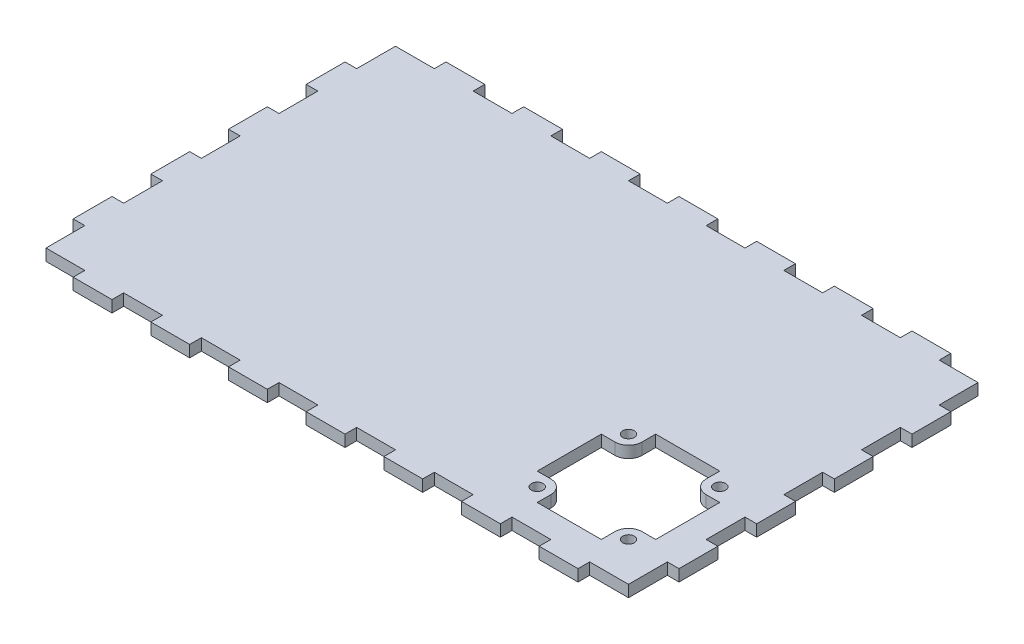
SolidWorks part; units mm, degrees
ref_plane "Front Plane" through (0, 0, 0) normal (0, 0, 1) x (1, 0, 0)
ref_plane "Top Plane" through (0, 0, 0) normal (0, 1, 0) x (1, 0, 0)
ref_plane "Right Plane" through (0, 0, 0) normal (1, 0, 0) x (0, 0, -1)
sketch "Sketch1" plane through (0, 0, 0) normal (0, 1, 0) x (1, 0, 0)
  line L0 (15, 45) -> (25, 48) construction
  line L1 (-76.5, 46.5) -> (76.5, 46.5) construction
  line L2 (-76.5, 46.5) -> (-76.5, -46.5) construction
  line L3 (-76.5, -46.5) -> (76.5, -46.5) construction
  line L4 (76.5, 46.5) -> (76.5, -46.5) construction
  line L5 (-76.5, 46.5) -> (76.5, -46.5) construction
  line L6 (-76.5, -46.5) -> (76.5, 46.5) construction
  line L7 (-5, 48) -> (5, 48)
  line L8 (-5, 48) -> (-5, 45)
  line L9 (-5, 45) -> (5, 45) construction
  line L10 (5, 48) -> (5, 45)
  line L11 (-5, 48) -> (5, 45) construction
  line L12 (-5, 45) -> (5, 48) construction
  line L13 (15, 45) -> (25, 45) construction
  line L14 (15, 48) -> (25, 45) construction
  line L15 (25, 48) -> (25, 45)
  line L16 (15, 48) -> (25, 48)
  line L17 (15, 48) -> (15, 45)
  line L18 (35, 45) -> (45, 48) construction
  line L19 (35, 45) -> (45, 45) construction
  line L20 (35, 48) -> (45, 45) construction
  line L21 (45, 48) -> (45, 45)
  line L22 (35, 48) -> (45, 48)
  line L23 (35, 48) -> (35, 45)
  line L24 (55, 45) -> (65, 48) construction
  line L25 (55, 45) -> (65, 45) construction
  line L26 (55, 48) -> (65, 45) construction
  line L27 (65, 48) -> (65, 45)
  line L28 (55, 48) -> (65, 48)
  line L29 (55, 48) -> (55, 45)
  line L30 (-25, 45) -> (-15, 48) construction
  line L31 (-25, 45) -> (-15, 45) construction
  line L32 (-25, 48) -> (-15, 45) construction
  line L33 (-15, 48) -> (-15, 45)
  line L34 (-25, 48) -> (-15, 48)
  line L35 (-25, 48) -> (-25, 45)
  line L36 (-45, 45) -> (-35, 48) construction
  line L37 (-45, 45) -> (-35, 45) construction
  line L38 (-45, 48) -> (-35, 45) construction
  line L39 (-35, 48) -> (-35, 45)
  line L40 (-45, 48) -> (-35, 48)
  line L41 (-45, 48) -> (-45, 45)
  line L42 (-65, 45) -> (-55, 48) construction
  line L43 (-65, 45) -> (-55, 45) construction
  line L44 (-65, 48) -> (-55, 45) construction
  line L45 (-55, 48) -> (-55, 45)
  line L46 (-65, 48) -> (-55, 48)
  line L47 (-65, 48) -> (-65, 45)
  line L48 (-55, 45) -> (-45, 45)
  line L49 (-35, 45) -> (-25, 45)
  line L50 (-15, 45) -> (-5, 45)
  line L51 (5, 45) -> (15, 45)
  line L52 (25, 45) -> (35, 45)
  line L53 (45, 45) -> (55, 45)
  line L54 (55, 48) -> (45, 48) construction
  line L55 (0, 0) -> (9.7796, 0) construction
  line L56 (0, 0) -> (0, 12.2502) construction
  line L57 (65, -48) -> (65, -45)
  line L58 (55, -48) -> (65, -48)
  line L59 (55, -48) -> (55, -45)
  line L60 (45, -45) -> (55, -45)
  line L61 (45, -48) -> (45, -45)
  line L62 (35, -48) -> (45, -48)
  line L63 (35, -48) -> (35, -45)
  line L64 (25, -45) -> (35, -45)
  line L65 (25, -48) -> (25, -45)
  line L66 (15, -48) -> (25, -48)
  line L67 (15, -48) -> (15, -45)
  line L68 (5, -45) -> (15, -45)
  line L69 (5, -48) -> (5, -45)
  line L70 (-5, -48) -> (5, -48)
  line L71 (-5, -48) -> (-5, -45)
  line L72 (-15, -45) -> (-5, -45)
  line L73 (-15, -48) -> (-15, -45)
  line L74 (-25, -48) -> (-15, -48)
  line L75 (-25, -48) -> (-25, -45)
  line L76 (-35, -45) -> (-25, -45)
  line L77 (-35, -48) -> (-35, -45)
  line L78 (-45, -48) -> (-35, -48)
  line L79 (-45, -48) -> (-45, -45)
  line L80 (-55, -45) -> (-45, -45)
  line L81 (-55, -48) -> (-55, -45)
  line L82 (-65, -48) -> (-65, -45)
  line L83 (-65, -48) -> (-55, -48)
  line L84 (-65, 45) -> (-75, 45)
  line L89 (-75, 45) -> (-75, 35)
  line L90 (-75, 25) -> (-75, 15)
  line L91 (-78, 25) -> (-75, 25)
  line L92 (-78, 25) -> (-78, 35)
  line L93 (-78, 35) -> (-75, 35)
  line L94 (-75, 25) -> (-75, 35) construction
  line L95 (-78, 25) -> (-75, 35) construction
  line L96 (-78, 35) -> (-75, 25) construction
  line L97 (-78, 5) -> (-75, 5)
  line L98 (-78, 5) -> (-75, 15) construction
  line L99 (-78, 5) -> (-78, 15)
  line L100 (-78, 15) -> (-75, 5) construction
  line L101 (-78, 15) -> (-75, 15)
  line L102 (-75, 5) -> (-75, 15) construction
  line L103 (-78, -15) -> (-75, -15)
  line L104 (-78, -15) -> (-75, -5) construction
  line L105 (-78, -15) -> (-78, -5)
  line L106 (-78, -5) -> (-75, -15) construction
  line L107 (-78, -5) -> (-75, -5)
  line L108 (-75, -15) -> (-75, -5) construction
  line L109 (-78, -35) -> (-75, -35)
  line L110 (-78, -35) -> (-75, -25) construction
  line L111 (-78, -35) -> (-78, -25)
  line L112 (-78, -25) -> (-75, -35) construction
  line L113 (-78, -25) -> (-75, -25)
  line L114 (-75, -35) -> (-75, -25) construction
  line L115 (-75, 5) -> (-75, -5)
  line L116 (-75, -15) -> (-75, -25)
  line L117 (-75, -35) -> (-75, -45)
  line L118 (-75, -45) -> (-65, -45)
  line L119 (65, 45) -> (75, 45)
  line L120 (65, -45) -> (75, -45)
  line L121 (75, -35) -> (75, -45)
  line L122 (78, -35) -> (75, -35)
  line L123 (78, -35) -> (78, -25)
  line L124 (78, -25) -> (75, -25)
  line L125 (75, -15) -> (75, -25)
  line L126 (78, -15) -> (75, -15)
  line L127 (78, -15) -> (78, -5)
  line L128 (78, -5) -> (75, -5)
  line L129 (75, 5) -> (75, -5)
  line L130 (78, 5) -> (75, 5)
  line L131 (78, 5) -> (78, 15)
  line L132 (78, 15) -> (75, 15)
  line L133 (75, 25) -> (75, 15)
  line L134 (78, 25) -> (75, 25)
  line L135 (78, 25) -> (78, 35)
  line L136 (78, 35) -> (75, 35)
  line L137 (75, 45) -> (75, 35)
  point P0 (0, 0)
  point P6 (0, 46.5)
  point P66 (-76.5, 30)
  dimension "D1" = 153
  dimension "D2" = 93
  dimension "D3" = 10
  dimension "D4" = 3
  dimension "D5" = 4
  dimension "D7" = 10
  dimension "D8" = 10
  dimension "D9" = 10
  dimension "D10" = 10
  dimension "D11" = 10
  dimension "D12" = 10
  dimension "D6" = 4
  dimension "D13" = 4
extrude "Boss-Extrude1" add sketch "Sketch1" along normal blind 3
sketch "Sketch3" plane through (0, 3, 0) normal (0, 1, 0) x (1, 0, 0)
  line L0 (41.5, -35) -> (41.5, -11.5) construction
  line L1 (41.5, -11.5) -> (65, -11.5) construction
  line L2 (65, -11.5) -> (65, -35) construction
  line L3 (65, -35) -> (41.5, -35) construction
  line L4 (45, -45) -> (55, -45) construction
  line L5 (75, -25) -> (75, -15) construction
  circle A0 centre (41.5, -11.5) radius 1.5
  circle A1 centre (65, -11.5) radius 1.5
  circle A2 centre (65, -35) radius 1.5
  circle A3 centre (41.5, -35) radius 1.5
  point P8 (61.6737, -9.3532)
  dimension "D1" = 3
  dimension "D2" = 3
  dimension "D3" = 3
  dimension "D4" = 3
  dimension "D5" = 23.5
  dimension "D6" = 23.5
  dimension "D7" = 10
  dimension "D8" = 10
extrude "Cut-Extrude2" cut sketch "Sketch3" against normal blind 3
sketch "Sketch4" plane through (0, 3, 0) normal (0, 1, 0) x (1, 0, 0)
  line L0 (41.5, -8) -> (65, -8) construction
  line L1 (38, -11.5) -> (38, -35) construction
  line L2 (41.5, -38.5) -> (65, -38.5) construction
  line L3 (68.5, -35) -> (68.5, -11.5) construction
  line L4 (45, -35) -> (45, -38.5)
  line L5 (61.5, -35) -> (61.5, -38.5)
  line L6 (65, -15) -> (68.5, -15)
  line L7 (65, -31.5) -> (68.5, -31.5)
  line L8 (41.5, -15) -> (38, -15)
  line L9 (41.5, -31.5) -> (38, -31.5)
  line L10 (45, -11.5) -> (45, -8)
  line L11 (61.5, -11.5) -> (61.5, -8)
  line L12 (38, -15) -> (38, -31.5)
  line L13 (45, -38.5) -> (61.5, -38.5)
  line L14 (68.5, -31.5) -> (68.5, -15)
  line L15 (61.5, -8) -> (45, -8)
  circle A0 centre (41.5, -11.5) radius 3.5 construction
  circle A1 centre (65, -11.5) radius 3.5 construction
  circle A2 centre (65, -35) radius 3.5 construction
  circle A3 centre (41.5, -35) radius 3.5 construction
  arc A4 (61.5, -35) -> (65, -31.5) centre (65, -35) cw
  arc A5 (65, -15) -> (61.5, -11.5) centre (65, -11.5) cw
  arc A6 (41.5, -15) -> (45, -11.5) centre (41.5, -11.5) ccw
  arc A7 (41.5, -31.5) -> (45, -35) centre (41.5, -35) cw
  dimension "D1" = 7
  dimension "D2" = 7
  dimension "D3" = 7
  dimension "D4" = 7
extrude "Cut-Extrude3" cut sketch "Sketch4" against normal blind 3
